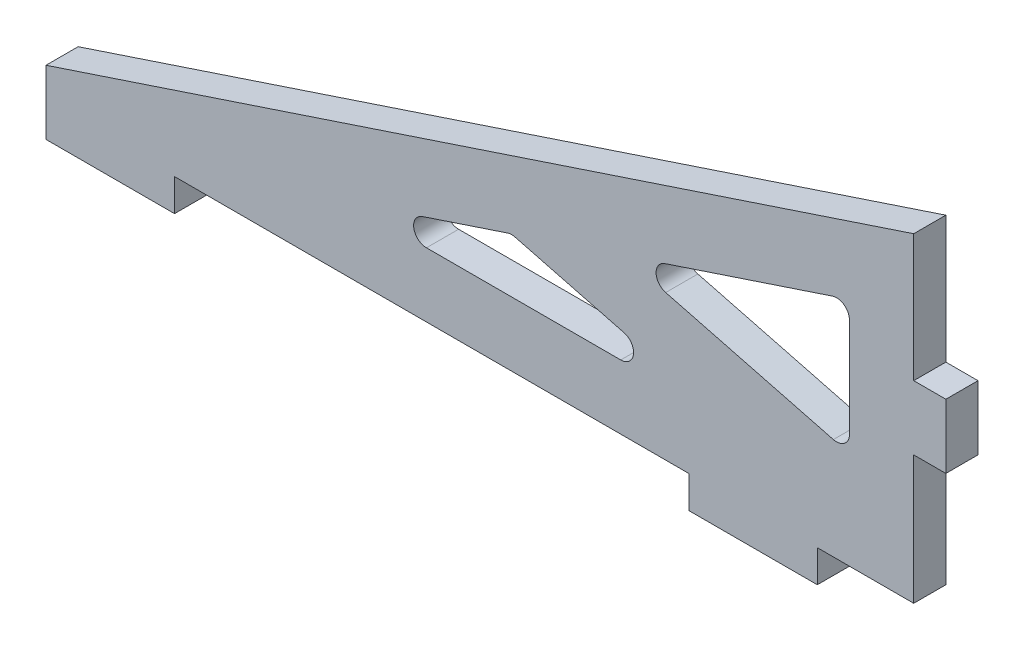
SolidWorks part; units mm, degrees
ref_plane "Front Plane" through (0, 0, 0) normal (0, 0, 1) x (1, 0, 0)
ref_plane "Top Plane" through (0, 0, 0) normal (0, 1, 0) x (1, 0, 0)
ref_plane "Right Plane" through (0, 0, 0) normal (1, 0, 0) x (0, 0, -1)
sketch "Sketch2" plane through (0, 0, 0) normal (0, 0, 1) x (1, 0, 0)
  line L0 (-92.95, 148.308) -> (78.5, 205.204)
  line L1 (78.5, 205.204) -> (84.85, 205.204) construction
  line L2 (84.85, 205.204) -> (84.85, 180.058) construction
  line L4 (-118.35, 135.608) -> (-118.35, 141.958) construction
  line L5 (84.85, 167.358) -> (84.85, 141.958) construction
  line L6 (84.85, 180.058) -> (78.5, 180.058)
  line L8 (84.85, 167.358) -> (78.5, 167.358)
  line L9 (78.5, 180.058) -> (78.5, 167.358) construction
  line L10 (-92.95, 135.608) -> (-92.95, 148.308) construction
  line L13 (-67.55, 141.958) -> (-67.55, 135.608)
  line L15 (34.05, 135.608) -> (34.05, 141.958)
  line L17 (59.45, 141.958) -> (59.45, 135.608)
  line L19 (-92.95, 135.608) -> (-118.35, 135.608) construction
  line L20 (-92.95, 141.958) -> (-92.95, 135.608)
  line L21 (-92.95, 141.958) -> (-92.95, 148.308)
  line L22 (-92.95, 135.608) -> (-67.55, 135.608)
  line L23 (-67.55, 141.958) -> (34.05, 141.958)
  line L24 (34.05, 135.608) -> (59.45, 135.608)
  line L25 (59.45, 141.958) -> (78.5, 141.958)
  line L26 (78.5, 167.358) -> (78.5, 141.958)
  line L27 (84.85, 167.358) -> (84.85, 180.058)
  line L28 (78.5, 180.058) -> (78.5, 205.204)
  dimension "D1" = 6.35
  dimension "D2" = 6.35
  dimension "D3" = 6.35
  dimension "D4" = 12.7
  dimension "D5" = 6.35
  dimension "D6" = 25.4
  dimension "D7" = 25.4
  dimension "D8" = 25.4
  dimension "D9" = 25.4
  dimension "D10" = 6.35
  dimension "D11" = 25.4
extrude "Boss-Extrude1" add sketch "Sketch2" along normal blind 6.35
sketch "Sketch3" plane through (0, 0, 6.35) normal (0, 0, 1) x (1, 0, 0)
  line L0 (-33.4926, 154.658) -> (65.8, 187.6084)
  line L1 (65.8, 187.6084) -> (65.8, 154.658)
  line L2 (65.8, 154.658) -> (-33.4926, 154.658)
  line L3 (78.5, 205.204) -> (-92.95, 148.308) construction
  line L4 (-67.55, 141.958) -> (34.05, 141.958) construction
  line L6 (65.8, 154.658) -> (-19.3713, 176.756) construction
  line L7 (64.2053, 148.5115) -> (-20.9661, 170.6095)
  line L8 (67.3947, 160.8045) -> (-17.7766, 182.9025)
  line L9 (78.5, 180.058) -> (78.5, 205.204) construction
  arc A0 (64.2053, 148.5115) -> (67.3947, 160.8045) centre (65.8, 154.658) ccw
  arc A1 (-17.7766, 182.9025) -> (-20.9661, 170.6095) centre (-19.3713, 176.756) ccw
  point P10 (23.2143, 165.707)
  dimension "D4" = 6.35
  dimension "D1" = 12.7
  dimension "D2" = 12.7
  dimension "D3" = 12.7
extrude "Cut-Extrude1" cut sketch "Sketch3" against normal through all contours L2 L7 L0 | L8 L1 L0
fillet "Fillet1" radius 2.54 6 edges at (65.8, 187.6084, 3.175) (21.1696, 172.7978, 3.175) (-1.0194, 165.4343, 3.175) (40.5151, 154.658, 3.175) (-33.4926, 154.658, 3.175) (65.8, 161.2182, 3.175)
